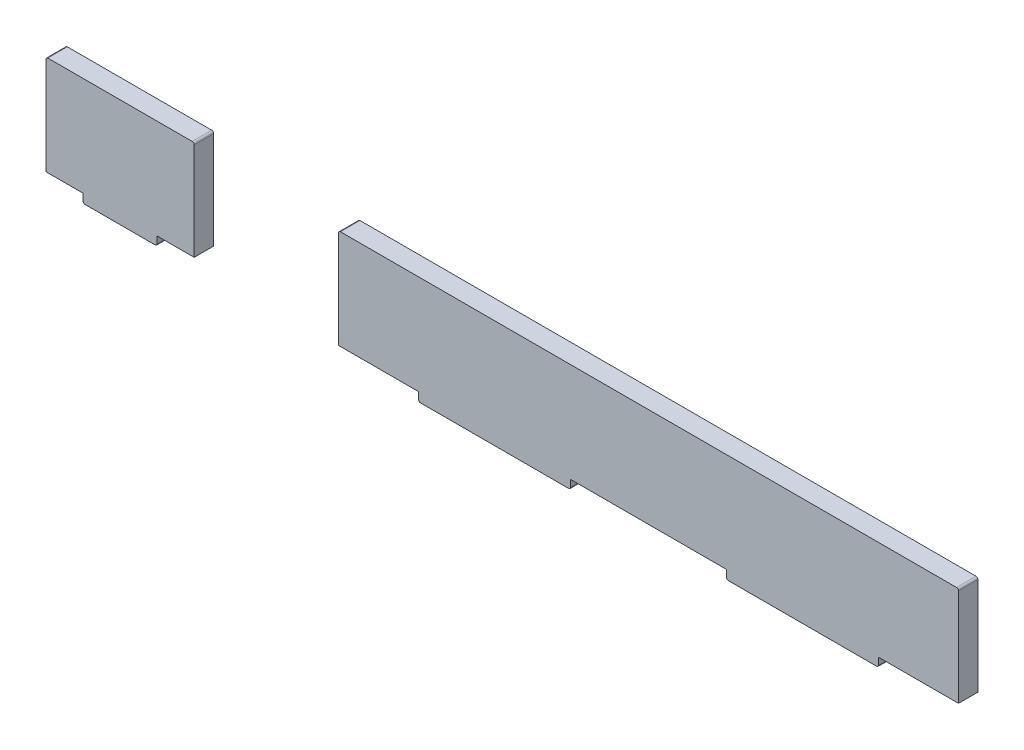
SolidWorks part; units mm, degrees
ref_plane "Front Plane" through (0, 0, 0) normal (0, 0, 1) x (1, 0, 0)
ref_plane "Top Plane" through (0, 0, 0) normal (0, 1, 0) x (1, 0, 0)
ref_plane "Right Plane" through (0, 0, 0) normal (1, 0, 0) x (0, 0, -1)
sketch "Sketch1" plane through (0, 0, 0) normal (0, 0, 1) x (1, 0, 0)
  line L0 (-93.1181, 2.1039) -> (-74.1181, 2.1039)
  line L1 (-149.1181, 53.1039) -> (-75.1181, 53.1039)
  line L2 (-150.1181, 52.1039) -> (-150.1181, 2.1039)
  line L3 (-150.1181, 2.1039) -> (-131.1181, 2.1039)
  line L4 (-74.1181, 52.1039) -> (-74.1181, 2.1039)
  line L5 (119, 0) -> (199, 0)
  line L6 (-131.1181, 2.1039) -> (-131.1181, -1.3961)
  line L7 (-130.1181, -2.3961) -> (-94.1181, -2.3961)
  line L8 (-93.1181, 2.1039) -> (-93.1181, -1.3961)
  line L9 (1, 51) -> (317, 51)
  line L10 (0, 50) -> (0, 0)
  line L11 (0, 0) -> (41, 0)
  line L12 (318, 50) -> (318, 0)
  line L13 (277, 0) -> (318, 0)
  line L14 (41, 0) -> (41, -3.5)
  line L15 (42, -4.5) -> (118, -4.5)
  line L16 (119, 0) -> (119, -3.5)
  line L18 (199, 0) -> (199, -3.5)
  line L19 (200, -4.5) -> (276, -4.5)
  line L20 (277, 0) -> (277, -3.5)
  arc A0 (-149.1181, 53.1039) -> (-150.1181, 52.1039) centre (-149.1181, 52.1039) ccw
  arc A1 (-130.1181, -2.3961) -> (-131.1181, -1.3961) centre (-130.1181, -1.3961) cw
  arc A2 (-94.1181, -2.3961) -> (-93.1181, -1.3961) centre (-94.1181, -1.3961) ccw
  arc A3 (-74.1181, 52.1039) -> (-75.1181, 53.1039) centre (-75.1181, 52.1039) ccw
  arc A4 (277, -3.5) -> (276, -4.5) centre (276, -3.5) cw
  arc A5 (200, -4.5) -> (199, -3.5) centre (200, -3.5) cw
  arc A6 (119, -3.5) -> (118, -4.5) centre (118, -3.5) cw
  arc A7 (42, -4.5) -> (41, -3.5) centre (42, -3.5) cw
  arc A8 (318, 50) -> (317, 51) centre (317, 50) ccw
  arc A9 (1, 51) -> (0, 50) centre (1, 50) ccw
  point P8 (-112.1181, -2.3961)
  point P9 (-112.1181, 53.1039)
  point P22 (159, 0)
  point P23 (159, 51)
  point P24 (0, 0)
  point P25 (0, 0)
  point P26 (-75.1181, 2.1039)
  point P32 (-130.6841, 59.6771)
  point P41 (-130.894, 58.6802)
  point P42 (-131.6039, 58.7063)
  point P55 (41, -1.75)
  point P56 (0, 14.8531)
  point P57 (0, 0)
  point P58 (200.44, -27.5211)
  point P59 (316.734, -38.2989)
  point P60 (322.9414, 18.6801)
  point P61 (207.4722, -41.3275)
  dimension "D2" = 1
  dimension "D3" = 1
  dimension "D17" = 1
  dimension "D4" = 38
  dimension "D5" = 78
  dimension "D6" = 78
  dimension "D7" = 41
  dimension "D8" = 50
  dimension "D9" = 4.5
  dimension "D14" = 76
  dimension "D15" = 50
  dimension "D16" = 4.5
  dimension "D18" = 316
extrude "Boss-Extrude1" add sketch "Sketch1" along normal blind 10
